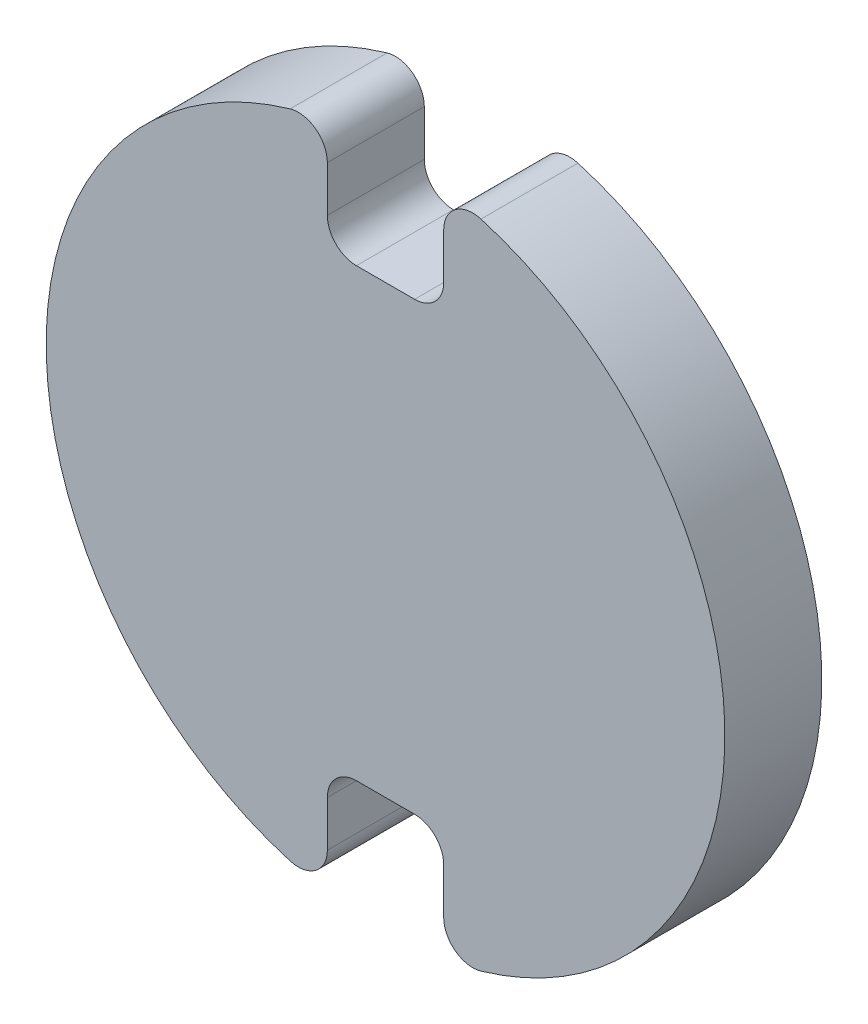
SolidWorks part; units mm, degrees
ref_plane "Ön Düzlem" through (0, 0, 0) normal (0, 0, 1) x (1, 0, 0)
ref_plane "Üst Düzlem" through (0, 0, 0) normal (0, 1, 0) x (1, 0, 0)
ref_plane "Sağ Düzlem" through (0, 0, 0) normal (1, 0, 0) x (0, 0, -1)
sketch "Çizim1" plane through (0, 0, 0) normal (0, 0, 1) x (1, 0, 0)
  circle A0 centre (0, 0) radius 35
  dimension "D1" = 70
extrude "Yükseklik-Ekstrüzyon1" add sketch "Çizim1" along normal blind 10
sketch "Çizim2" plane through (0, 0, 0) normal (0, 0, -1) x (-1, 0, 0)
  line L0 (0, 35) -> (0, -35) construction
  line L2 (-6, 35) -> (6, 35)
  line L3 (-6, 35) -> (-6, 23)
  line L4 (-6, 23) -> (6, 23)
  line L5 (6, 35) -> (6, 23)
  line L6 (-6, 35) -> (6, 23) construction
  line L7 (-6, 23) -> (6, 35) construction
  line L8 (-6, -23) -> (6, -23)
  line L9 (-6, -23) -> (-6, -35)
  line L10 (-6, -35) -> (6, -35)
  line L11 (6, -23) -> (6, -35)
  line L12 (-6, -23) -> (6, -35) construction
  line L13 (-6, -35) -> (6, -23) construction
  circle A0 centre (0, 0) radius 35 construction
  point P5 (0, 29)
  point P10 (0, -29)
  dimension "D1" = 12
  dimension "D2" = 12
  dimension "D3" = 12
  dimension "D4" = 12
extrude "Kes-Ekstrüzyon1" cut sketch "Çizim2" against normal blind 16
fillet "Radyus1" radius 3 8 edges at (-6, -34.4819, 5) (-6, -23, 5) (6, -23, 5) (6, -34.4819, 5) (6, 34.4819, 5) (-6, 34.4819, 5) (-6, 23, 5) (6, 23, 5)
